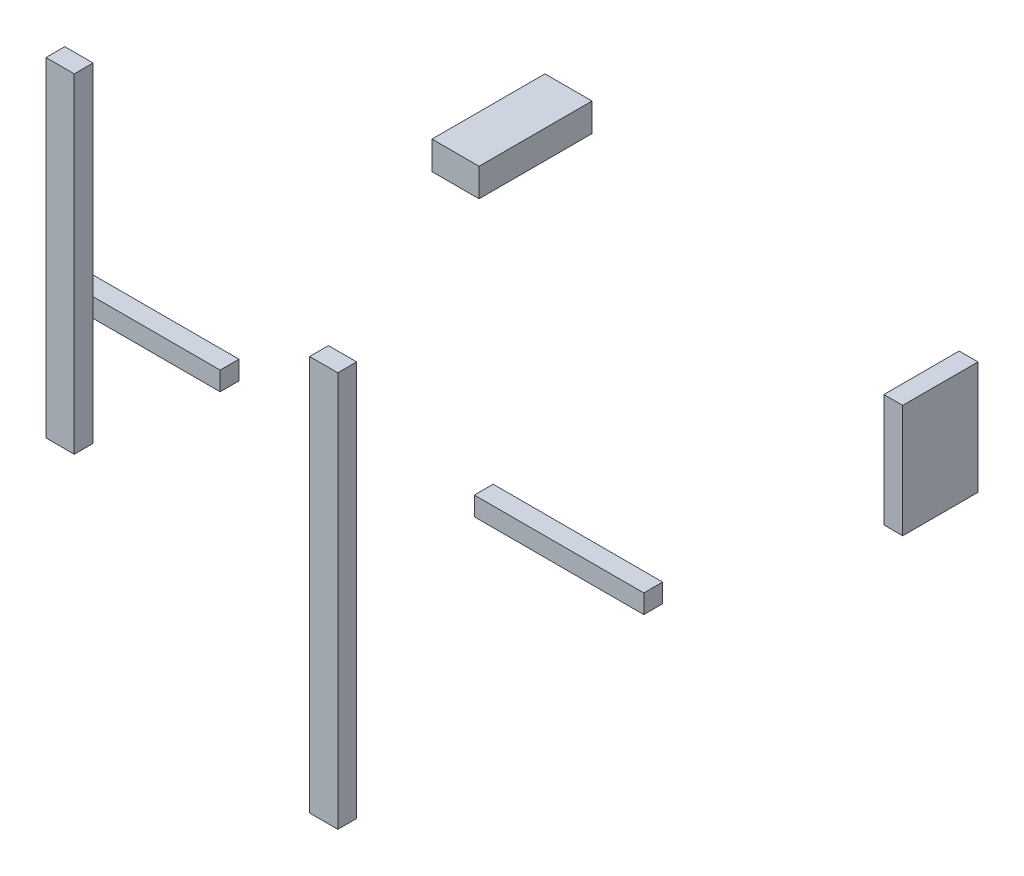
SolidWorks part; units mm, degrees
ref_plane "前视基准面" through (0, 0, 0) normal (0, 0, 1) x (1, 0, 0)
ref_plane "上视基准面" through (0, 0, 0) normal (0, 1, 0) x (1, 0, 0)
ref_plane "右视基准面" through (0, 0, 0) normal (1, 0, 0) x (0, 0, -1)
other "Configuration Table"
sketch "草图1" plane through (0, 0, 0) normal (0, 0, 1) x (1, 0, 0)
  line L1 (-1.5, -47) -> (1.5, -47)
  line L2 (-1.5, -47) -> (-1.5, -5)
  line L3 (-1.5, -5) -> (1.5, -5)
  line L4 (1.5, -47) -> (1.5, -5)
  line L5 (-1.5, -47) -> (1.5, -5) construction
  line L6 (-1.5, -5) -> (1.5, -47) construction
  point P0 (0, -26)
extrude "sensor cable: HC-SR04 to ESP32" add sketch "草图1" along normal blind 2 from offset 36 separate body
sketch "草图2" plane through (0, 0, 0) normal (0, 0, 1) x (1, 0, 0)
  line L1 (-19.5, -16.5) -> (-16.5, -16.5)
  line L2 (-19.5, -16.5) -> (-19.5, 18.5)
  line L3 (-19.5, 18.5) -> (-16.5, 18.5)
  line L4 (-16.5, -16.5) -> (-16.5, 18.5)
  line L5 (-19.5, -16.5) -> (-16.5, 18.5) construction
  line L6 (-19.5, 18.5) -> (-16.5, -16.5) construction
  point P0 (-18, 1)
extrude "servo PWM cable: SG90 to ESP32" add sketch "草图2" along normal blind 2 from offset 46 separate body
sketch "草图3" plane through (0, 0, 0) normal (0, 0, 1) x (1, 0, 0)
  line L1 (-30, -14) -> (-12, -14)
  line L2 (-30, -14) -> (-30, -12)
  line L3 (-30, -12) -> (-12, -12)
  line L4 (-12, -14) -> (-12, -12)
  line L5 (-30, -14) -> (-12, -12) construction
  line L6 (-30, -12) -> (-12, -14) construction
  point P0 (-21, -13)
extrude "LED data cable: WS2812 to ESP32" add sketch "草图3" along normal blind 2 from offset 35 separate body
sketch "草图4" plane through (0, 0, 0) normal (0, 0, 1) x (1, 0, 0)
  line L1 (13, -14) -> (31, -14)
  line L2 (13, -14) -> (13, -12)
  line L3 (13, -12) -> (31, -12)
  line L4 (31, -14) -> (31, -12)
  line L5 (13, -14) -> (31, -12) construction
  line L6 (13, -12) -> (31, -14) construction
  point P0 (22, -13)
extrude "buzzer signal cable: buzzer to ESP32" add sketch "草图4" along normal blind 2 from offset 33 separate body
sketch "草图5" plane through (0, 0, 0) normal (0, 0, 1) x (1, 0, 0)
  line L1 (-2.5, 4.5) -> (2.5, 4.5)
  line L2 (-2.5, 4.5) -> (-2.5, 7.5)
  line L3 (-2.5, 7.5) -> (2.5, 7.5)
  line L4 (2.5, 4.5) -> (2.5, 7.5)
  line L5 (-2.5, 4.5) -> (2.5, 7.5) construction
  line L6 (-2.5, 7.5) -> (2.5, 4.5) construction
  point P0 (0, 6)
extrude "5V power leads: battery to main rail" add sketch "草图5" along normal blind 12 from offset 12 separate body
sketch "草图6" plane through (0, 0, 0) normal (0, 0, 1) x (1, 0, 0)
  line L1 (49.5, 0) -> (51.5, 0)
  line L2 (49.5, 0) -> (49.5, 12)
  line L3 (49.5, 12) -> (51.5, 12)
  line L4 (51.5, 0) -> (51.5, 12)
  line L5 (49.5, 0) -> (51.5, 12) construction
  line L6 (49.5, 12) -> (51.5, 0) construction
  point P0 (50.5, 6)
extrude "USB side exit clearance marker" add sketch "草图6" along normal blind 8 from offset 20 separate body
